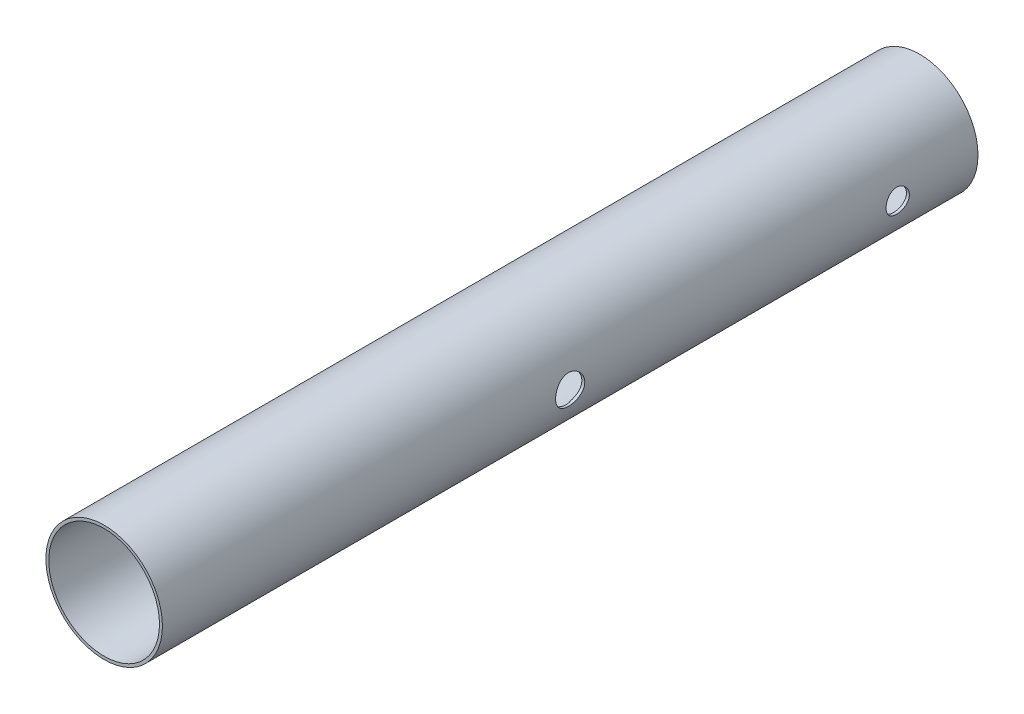
SolidWorks part; units mm, degrees
ref_plane "Plano frontal" through (0, 0, 0) normal (0, 0, 1) x (1, 0, 0)
ref_plane "Plano superior" through (0, 0, 0) normal (0, 1, 0) x (1, 0, 0)
ref_plane "Plano direito" through (0, 0, 0) normal (1, 0, 0) x (0, 0, -1)
sketch "Esboço2" plane through (0, 0, 0) normal (0, 0, 1) x (1, 0, 0)
  circle A0 centre (0, 0) radius 100
  circle A1 centre (0, 0) radius 95
extrude "Ressalto-extrusão2" add sketch "Esboço2" along normal blind 1400
sketch "Esboço3" plane through (0, 0, 0) normal (1, 0, 0) x (0, 0, -1)
  line L0 (-700, 100) -> (-700, -100) construction
  line L1 (0, 100) -> (-1400, 100) construction
  line L2 (-1400, -100) -> (0, -100) construction
  circle A0 centre (-700, 0) radius 25
  point P2 (0, 0)
  dimension "D1" = 50
extrude "Corte-extrusão1" cut sketch "Esboço3" against normal through all both and the other way through all
sketch "Esboço4" plane through (0, 0, 0) normal (1, 0, 0) x (0, 0, -1)
  line L1 (-692.9789, 28.898) -> (-707.0211, 28.898)
  line L2 (-692.9789, 28.898) -> (-692.9789, -28.898)
  line L3 (-692.9789, -28.898) -> (-707.0211, -28.898)
  line L4 (-707.0211, 28.898) -> (-707.0211, -28.898)
  line L5 (-692.9789, 28.898) -> (-707.0211, -28.898) construction
  line L6 (-692.9789, -28.898) -> (-707.0211, 28.898) construction
  circle A0 centre (-700, 0) radius 25 construction
  point P4 (-700, 0)
  point P5 (0, 0)
extrude "Corte-extrusão2" cut sketch "Esboço4" against normal mid plane 185
sketch "Esboço5" plane through (0, 0, 0) normal (1, 0, 0) x (0, 0, -1)
  circle A0 centre (-137.8261, 0) radius 20
  dimension "D1" = 40
extrude "Corte-extrusão3" cut sketch "Esboço5" along normal blind 185
